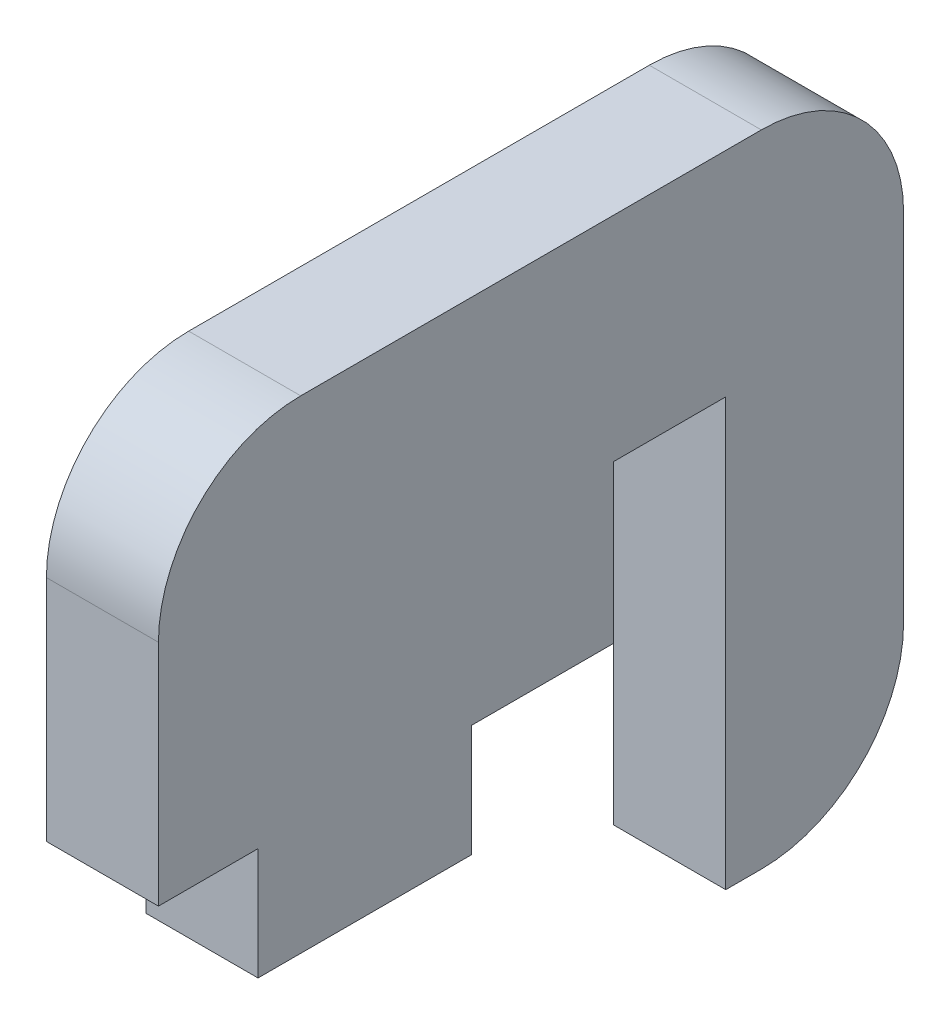
SolidWorks part; units mm, degrees
material "Hexcel AS4C (3000 Filaments)"
ref_plane "Front Plane" through (0, 0, 0) normal (1, 0, 0) x (0, 1, 0)
ref_plane "Top Plane" through (0, 0, 0) normal (0, 0, 1) x (0, 1, 0)
ref_plane "Right Plane" through (0, 0, 0) normal (0, 1, 0) x (-1, 0, 0)
sketch "Sketch1" plane through (0, 0, 0) normal (1, 0, 0) x (0, 1, 0)
  line L0 (0, 0) -> (4, 0)
  line L1 (4, 0) -> (4, 3.556)
  line L2 (4, 3.556) -> (12.16, 3.556)
  line L3 (17.24, -1.524) -> (17.24, -17.97)
  line L4 (12.16, -23.05) -> (-0.54, -23.05)
  line L5 (-5.62, -17.97) -> (-5.62, -16.7)
  line L6 (-5.62, -16.7) -> (9.62, -16.7)
  line L7 (9.62, -16.7) -> (9.62, -12.7)
  line L8 (9.62, -12.7) -> (4, -12.7)
  line L9 (4, -12.7) -> (4, -7.62)
  line L10 (4, -7.62) -> (0, -7.62)
  line L11 (0, -7.62) -> (0, 0)
  arc A0 (-0.54, -23.05) -> (-5.62, -17.97) centre (-0.54, -17.97) cw
  arc A1 (17.24, -17.97) -> (12.16, -23.05) centre (12.16, -17.97) cw
  arc A2 (12.16, 3.556) -> (17.24, -1.524) centre (12.16, -1.524) cw
  point P5 (2, -16.7)
  point P14 (2, -7.62)
  dimension "D9" = 5.08
  dimension "D1" = 7.62
  dimension "D2" = 5.08
  dimension "D3" = 4
  dimension "D4" = 4
  dimension "D5" = 3.556
  dimension "D6" = 7.62
  dimension "D7" = 6.35
  dimension "D8" = 15.24
extrude "Boss-Extrude1" add sketch "Sketch1" along normal blind 4
